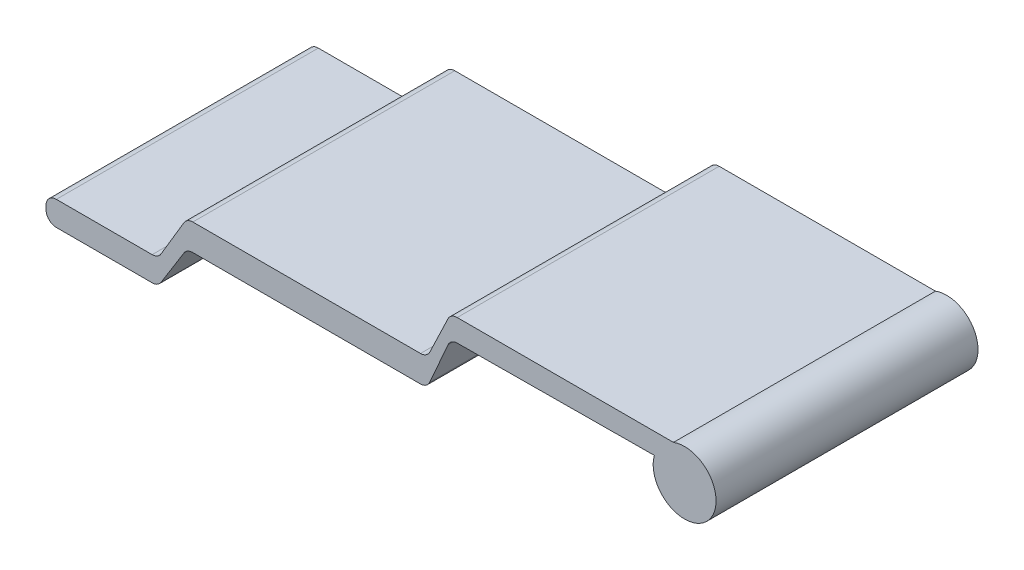
SolidWorks part; units mm, degrees
ref_plane "前视基准面" through (0, 0, 0) normal (0, 0, 1) x (1, 0, 0)
ref_plane "上视基准面" through (0, 0, 0) normal (0, 1, 0) x (1, 0, 0)
ref_plane "右视基准面" through (0, 0, 0) normal (1, 0, 0) x (0, 0, -1)
sketch "草图3" plane through (0, 0, 0) normal (0, 0, 1) x (1, 0, 0)
  line L0 (1.5, 0) -> (15.4151, 0)
  line L1 (0, 1.5) -> (0, 2.0364)
  line L2 (1.5, 3.5364) -> (15.396, 3.5364)
  line L3 (21.2783, 6.7492) -> (54.291, 6.7492)
  line L4 (21.2974, 10.5867) -> (54.3244, 10.5867)
  line L5 (16.685, 4.2693) -> (20.0084, 9.8538)
  line L6 (16.689, 0.7081) -> (20.0044, 6.0412)
  line L8 (59.6452, 17.7622) -> (91.1305, 17.7622)
  line L9 (55.6778, 11.4399) -> (58.2919, 16.9091)
  line L10 (55.6641, 7.6454) -> (58.3056, 13.6528)
  line L12 (91.1305, 14.7622) -> (59.6787, 14.549)
  arc A0 (91.1305, 14.7622) -> (92.6305, 16.2622) centre (91.1305, 16.2622) ccw
  arc A1 (91.1305, 17.7622) -> (92.6305, 16.2622) centre (91.1305, 16.2622) cw
  arc A2 (59.6787, 14.549) -> (58.3056, 13.6528) centre (59.6787, 13.049) ccw
  arc A3 (59.6452, 17.7622) -> (58.2919, 16.9091) centre (59.6452, 16.2622) ccw
  arc A4 (54.3244, 10.5867) -> (55.6778, 11.4399) centre (54.3244, 12.0867) ccw
  arc A5 (54.291, 6.7492) -> (55.6641, 7.6454) centre (54.291, 8.2492) ccw
  arc A6 (15.396, 3.5364) -> (16.685, 4.2693) centre (15.396, 5.0364) ccw
  arc A7 (15.4151, 0) -> (16.689, 0.7081) centre (15.4151, 1.5) ccw
  arc A8 (21.2783, 6.7492) -> (20.0044, 6.0412) centre (21.2783, 5.2492) ccw
  arc A9 (21.2974, 10.5867) -> (20.0084, 9.8538) centre (21.2974, 9.0867) ccw
  arc A10 (0, 2.0364) -> (1.5, 3.5364) centre (1.5, 2.0364) cw
  arc A11 (1.5, 0) -> (0, 1.5) centre (1.5, 1.5) cw
  circle A12 centre (92.6305, 13.4946) radius 4.5627
  point P16 (92.6305, 13.4946)
  point P37 (0, 0)
  dimension "D2" = 1.5
extrude "凸台-拉伸3" add sketch "草图3" along normal blind 38 contours A12 A0 A1 L8 A3 L9 A4 L4 A9 L5 A6 L2 A10 L1 A11 L0 A7 L6 A8 L3 A5 L10 A2 L12
